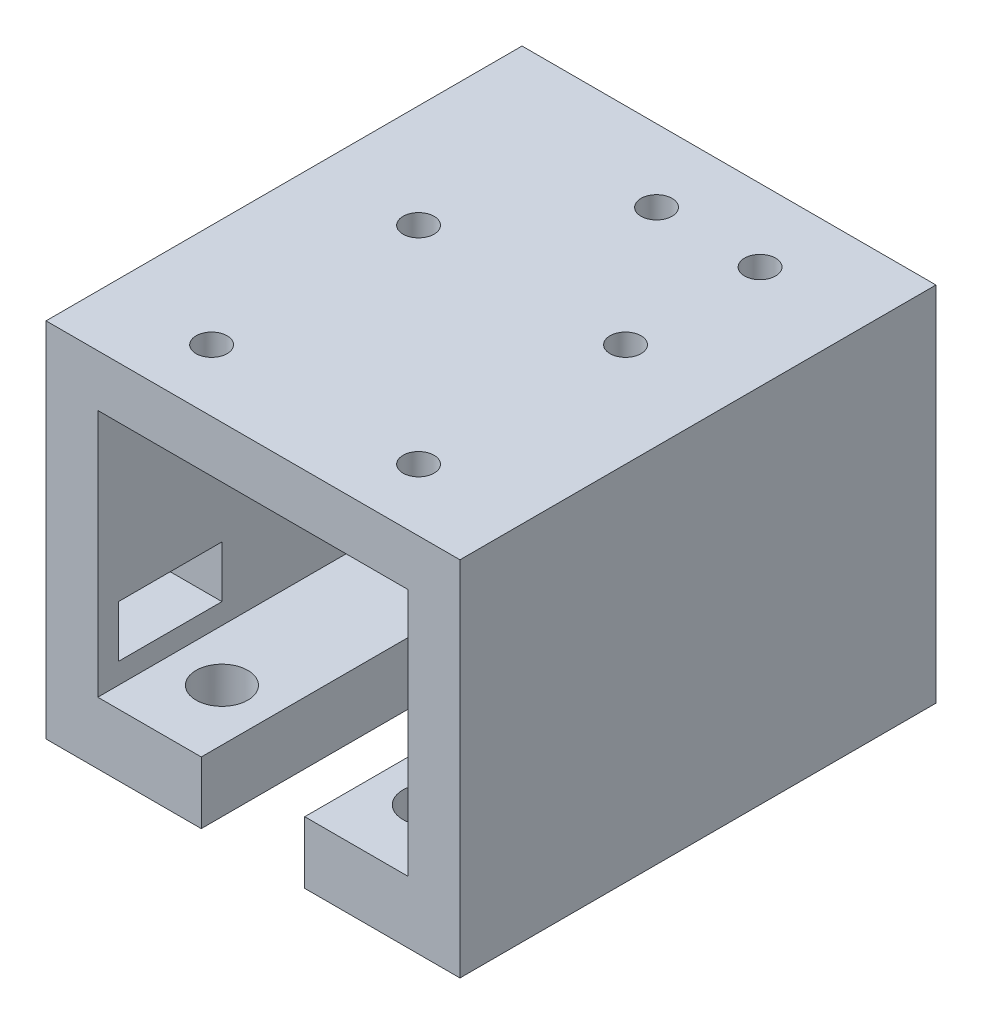
SolidWorks part; units mm, degrees
ref_plane "Front Plane" through (0, 0, 0) normal (0, 0, 1) x (1, 0, 0)
ref_plane "Top Plane" through (0, 0, 0) normal (0, 1, 0) x (1, 0, 0)
ref_plane "Right Plane" through (0, 0, 0) normal (1, 0, 0) x (0, 0, -1)
sketch "Sketch1" plane through (0, 0, 0) normal (0, 0, 1) x (1, 0, 0)
  line L0 (0, 22.6388) -> (0, -17.3328) construction
  line L1 (20, 39.0582) -> (-20, 39.0582)
  line L2 (-20, 39.0582) -> (-20, 4.0582)
  line L3 (-20, 4.0582) -> (-5, 4.0582)
  line L4 (-5, 4.0582) -> (-5, 10.0582)
  line L5 (-5, 10.0582) -> (-15, 10.0582)
  line L6 (-15, 10.0582) -> (-15, 34.0582)
  line L7 (-15, 34.0582) -> (15, 34.0582)
  line L8 (20, 4.0582) -> (5, 4.0582)
  line L9 (5, 4.0582) -> (5, 10.0582)
  line L10 (5, 10.0582) -> (15, 10.0582)
  line L11 (20, 39.0582) -> (20, 4.0582)
  line L12 (15, 10.0582) -> (15, 34.0582)
  point P11 (0, 39.0582)
  point P17 (0, 34.0582)
  dimension "D1" = 6
  dimension "D2" = 5
  dimension "D3" = 5
  dimension "D4" = 35
  dimension "D5" = 10
  dimension "D6" = 15
extrude "Boss-Extrude1" add sketch "Sketch1" along normal blind 46
sketch "Sketch2" plane through (0, 4.0582, 0) normal (0, -1, 0) x (-1, 0, 0)
  line L0 (20, -46) -> (5, -46) construction
  line L1 (20, -46) -> (20, 0) construction
  circle A0 centre (10, -39) radius 2.5
  circle A1 centre (-10, -39) radius 2.5
  circle A2 centre (-10, -7) radius 2.5
  circle A3 centre (10, -7) radius 2.5
  dimension "D1" = 5
  dimension "D2" = 7
  dimension "D3" = 10
  dimension "D4" = 2
  dimension "D5" = 2
extrude "Cut-Extrude1" cut sketch "Sketch2" against normal up to surface (6 mm away) up to face at (10, 10.0582, 23)
sketch "Sketch3" plane through (0, 39.0582, 0) normal (0, 1, 0) x (1, 0, 0)
  line L0 (-20, -46) -> (-20, 0) construction
  line L1 (20, 0) -> (-20, 0) construction
  circle A0 centre (-10, -20) radius 1.5
  circle A1 centre (10, -20) radius 1.5
  circle A2 centre (-10, -40) radius 1.5
  circle A3 centre (10, -40) radius 1.5
  dimension "D1" = 3
  dimension "D2" = 10
  dimension "D3" = 20
  dimension "D4" = 2
  dimension "D5" = 2
extrude "Cut-Extrude2" cut sketch "Sketch3" against normal up to surface (5 mm away) up to face at (0, 34.0582, 23)
sketch "Sketch4" plane through (0, 39.0582, 0) normal (0, 1, 0) x (1, 0, 0)
  line L0 (20, -46) -> (20, 0) construction
  line L1 (20, 0) -> (-20, 0) construction
  circle A0 centre (10, -7) radius 1.5
  circle A1 centre (0, -7) radius 1.5
  dimension "D1" = 3
  dimension "D2" = 10
  dimension "D3" = 7
  dimension "D4" = 2
extrude "Cut-Extrude3" cut sketch "Sketch4" against normal up to surface (5 mm away) up to face at (8.5, 34.0582, 40)
sketch "Sketch5" plane through (-20, 0, 0) normal (-1, 0, 0) x (0, 0, 1)
  line L0 (46, 4.0582) -> (0, 4.0582) construction
  line L1 (44, 12.0582) -> (34, 12.0582)
  line L2 (44, 12.0582) -> (44, 17.0582)
  line L3 (44, 17.0582) -> (34, 17.0582)
  line L4 (34, 12.0582) -> (34, 17.0582)
  line L5 (46, 39.0582) -> (46, 4.0582) construction
  dimension "D1" = 8
  dimension "D2" = 2
  dimension "D3" = 10
  dimension "D4" = 5
extrude "Cut-Extrude4" cut sketch "Sketch5" against normal up to surface (5 mm away) up to face at (-15, 22.0582, 23)
